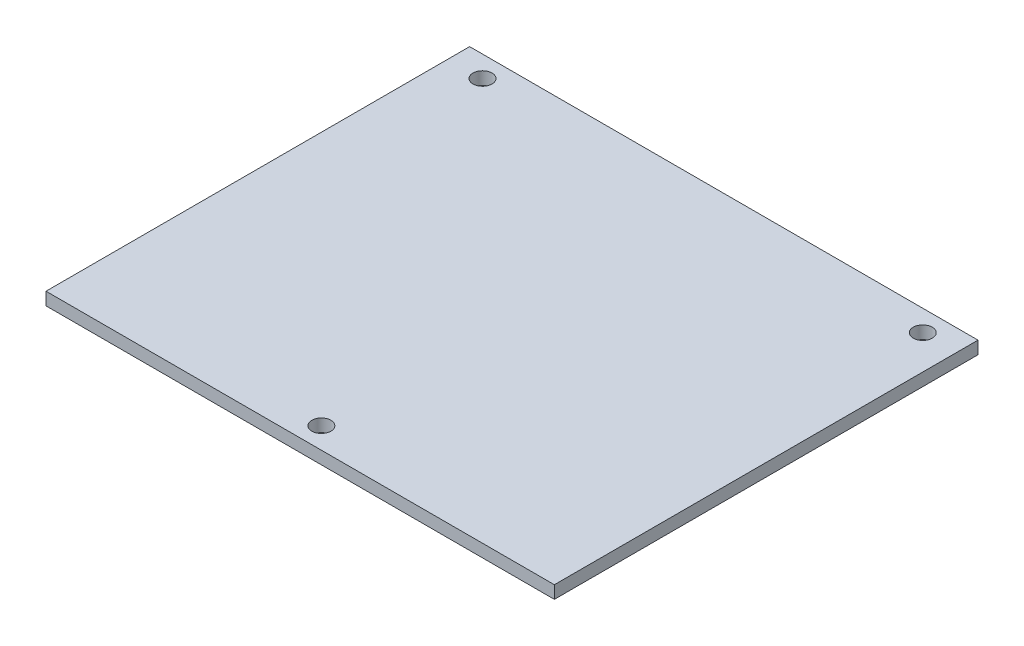
SolidWorks part; units mm, degrees
ref_plane "정면" through (0, 0, 0) normal (0, 0, 1) x (1, 0, 0)
ref_plane "윗면" through (0, 0, 0) normal (0, 1, 0) x (1, 0, 0)
ref_plane "우측면" through (0, 0, 0) normal (1, 0, 0) x (0, 0, -1)
sketch "스케치1" plane through (0, 0, 0) normal (0, 1, 0) x (1, 0, 0)
  line L1 (0, 0) -> (120, 0)
  line L2 (0, 0) -> (0, 100)
  line L3 (0, 100) -> (120, 100)
  line L4 (120, 0) -> (120, 100)
  dimension "D1" = 120
  dimension "D2" = 100
extrude "보스-돌출1" add sketch "스케치1" along normal blind 3
hole_wizard "M4 여유 구멍1" positions "스케치3" profile "스케치2" hole size "M4" standard "Ansi Metric"
sketch "스케치3" plane through (0, 3, 0) normal (0, 1, 0) x (1, 0, 0)
  line L9 (0, 0) -> (120, 0) construction
  line L10 (111.9615, 95) -> (8.0385, 95) construction
  line L11 (8.0385, 95) -> (60, 5) construction
  line L12 (60, 5) -> (111.9615, 95) construction
  line L15 (120, 100) -> (0, 100) construction
  line L16 (60, 95) -> (60, 100) construction
  point P0 (8.0385, 95)
  point P2 (111.9615, 95)
  point P4 (60, 5)
  dimension "D1" = 5
  dimension "D2" = 5
sketch "스케치2" plane through (8.0385, 3, -95) normal (1, 0, 0) x (0, 0, 1)
  line L0 (0, 0) -> (0, 21.3519)
  line L1 (0, 21.3519) -> (2.25, 20)
  line L2 (2.25, 20) -> (2.25, 0)
  line L5 (2.25, 0) -> (0, 0)
  line L10 (0, 21.3519) -> (-2.25, 20) construction
  line L11 (0, -6.35) -> (0, 107.95) construction
  dimension "구멍 지름" = 4.5
  dimension "구멍 깊이" = 20
  dimension "드릴 각도" = 118
